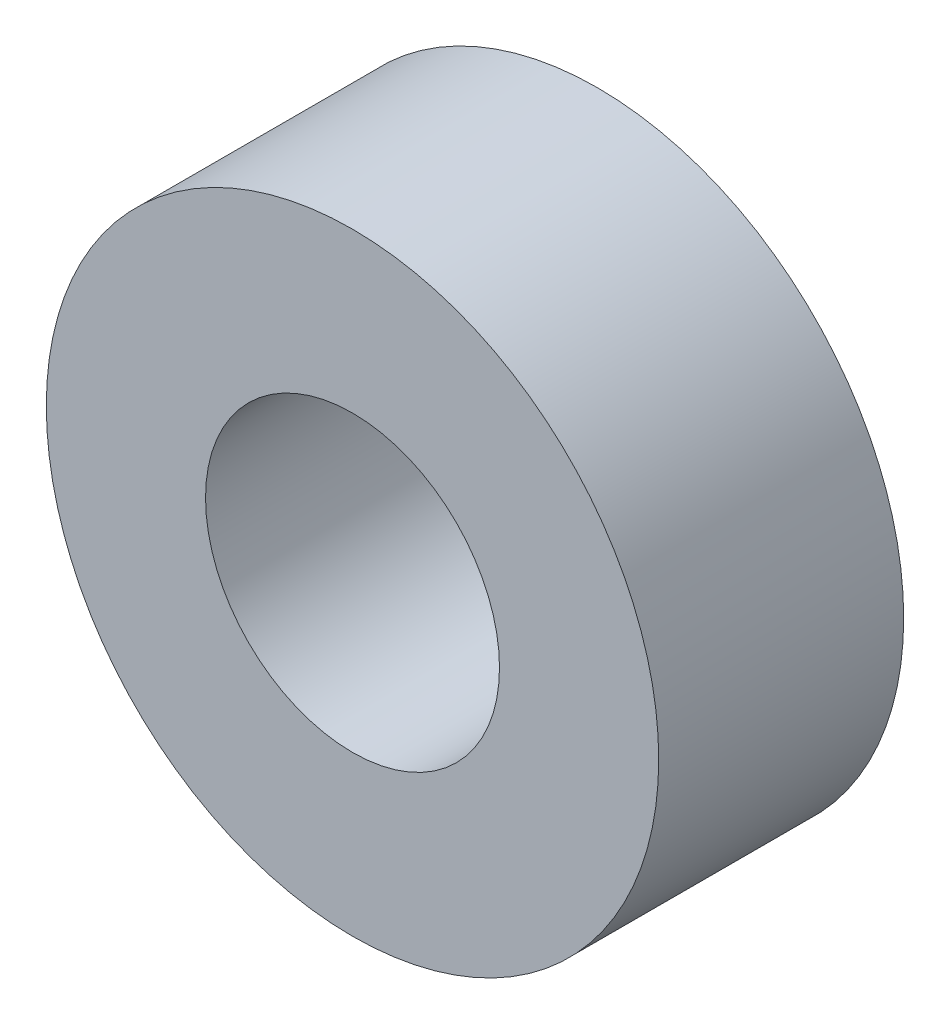
SolidWorks part; units mm, degrees
ref_plane "Front Plane" through (0, 0, 0) normal (0, 0, 1) x (1, 0, 0)
ref_plane "Top Plane" through (0, 0, 0) normal (0, 1, 0) x (1, 0, 0)
ref_plane "Right Plane" through (0, 0, 0) normal (1, 0, 0) x (0, 0, -1)
sketch "Sketch1" plane through (0, 0, 0) normal (0, 0, 1) x (1, 0, 0)
  circle A0 centre (0, 0) radius 3
  circle A1 centre (0, 0) radius 6.25
  dimension "D1" = 12.5
  dimension "D2" = 6
extrude "Boss-Extrude1" add sketch "Sketch1" along normal blind 5
